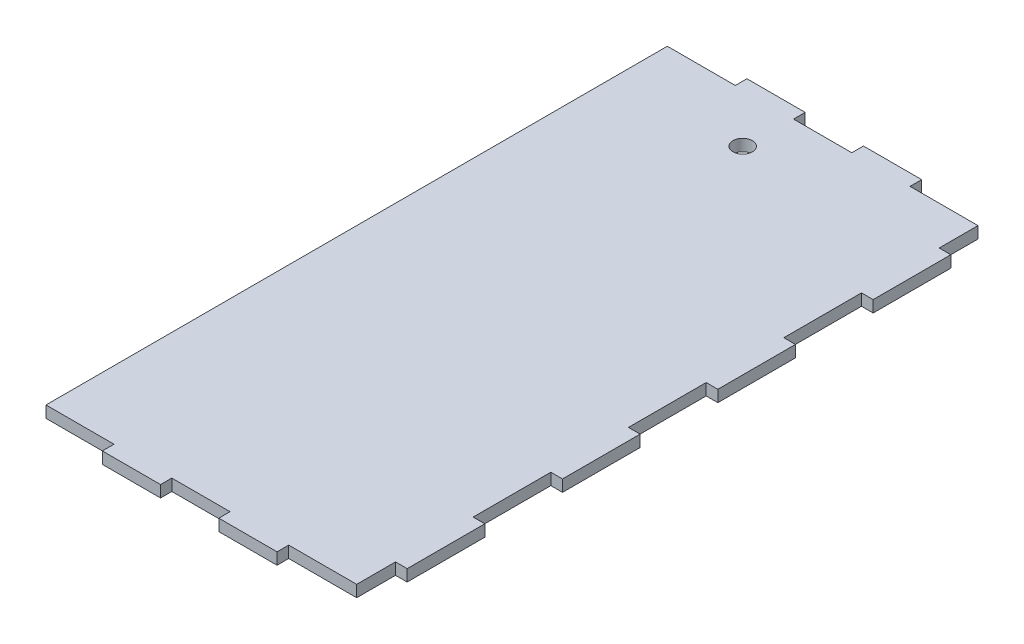
SolidWorks part; units mm, degrees
ref_plane "Alzado" through (0, 0, 0) normal (0, 0, 1) x (1, 0, 0)
ref_plane "Planta" through (0, 0, 0) normal (0, 1, 0) x (1, 0, 0)
ref_plane "Vista lateral" through (0, 0, 0) normal (1, 0, 0) x (0, 0, -1)
sketch "Croquis1" plane through (0, 0, 0) normal (0, 1, 0) x (1, 0, 0)
  line L0 (23, 3) -> (38, 3)
  line L1 (88.5, 16) -> (88.5, 36)
  line L2 (85.5, 166) -> (68, 166)
  line L3 (37.5, 153.3969) -> (37.5, 5.8969) construction
  line L4 (5.5, 153) -> (5.5, 13)
  line L5 (5.5, 73) -> (5.5, 93)
  line L6 (5.5, 166) -> (23, 166)
  line L7 (23, 166) -> (23, 169)
  line L8 (23, 169) -> (38, 169)
  line L9 (5.5, 113) -> (5.5, 133)
  line L10 (38, 169) -> (38, 166)
  line L11 (38, 166) -> (45.5, 166)
  line L12 (23, 166) -> (5.5, 166)
  line L13 (53, 169) -> (53, 166)
  line L14 (68, 169) -> (53, 169)
  line L15 (5.5, 53) -> (5.5, 33)
  line L16 (68, 166) -> (68, 169)
  line L17 (53, 166) -> (38, 166)
  line L18 (5.5, 153) -> (5.5, 166)
  line L19 (5.5, 13) -> (5.5, 6)
  line L20 (85.5, 156) -> (85.5, 153.3969)
  line L21 (53, 5.8969) -> (38, 5.8969)
  line L22 (38, 5.8969) -> (38, 3)
  line L23 (38, 3) -> (23, 3)
  line L24 (23, 3) -> (23, 6)
  line L25 (23, 6) -> (5.5, 6)
  line L26 (68, 6) -> (85.5, 6)
  line L27 (68, 3) -> (68, 6)
  line L28 (53, 5.8969) -> (53, 3)
  line L29 (85.5, 16) -> (85.5, 6)
  line L30 (85.5, 156) -> (85.5, 166)
  line L31 (85.5, 76) -> (88.5, 76)
  line L32 (88.5, 56) -> (85.5, 56)
  line L33 (85.5, 56) -> (85.5, 36)
  line L34 (85.5, 36) -> (88.5, 36)
  line L35 (88.5, 16) -> (85.5, 16)
  line L36 (88.5, 156) -> (85.5, 156)
  line L37 (85.5, 136) -> (88.5, 136)
  line L38 (85.5, 116) -> (85.5, 136)
  line L39 (88.5, 116) -> (85.5, 116)
  line L40 (85.5, 96) -> (88.5, 96)
  line L41 (85.5, 76) -> (85.5, 96)
  line L42 (88.5, 136) -> (88.5, 156)
  line L43 (53, 3) -> (68, 3)
  line L44 (88.5, 56) -> (88.5, 76)
  line L45 (88.5, 96) -> (88.5, 116)
  line L46 (85.5, 153.3969) -> (37.5, 153.3969) construction
  circle A0 centre (37.5, 153.3969) radius 2.5
  dimension "D4" = 5
  dimension "D2" = 80
  dimension "D3" = 80
  dimension "D5" = 3
  dimension "D6" = 20
  dimension "D7" = 3
  dimension "D8" = 147.5
  dimension "D9" = 3
  dimension "D10" = 15
  dimension "D11" = 17.5
  dimension "D12" = 160
  dimension "D13" = 15
  dimension "D14" = 10
  dimension "D15" = 10
  dimension "D16" = 48
extrude "Saliente-Extruir1" add sketch "Croquis1" along normal blind 3
